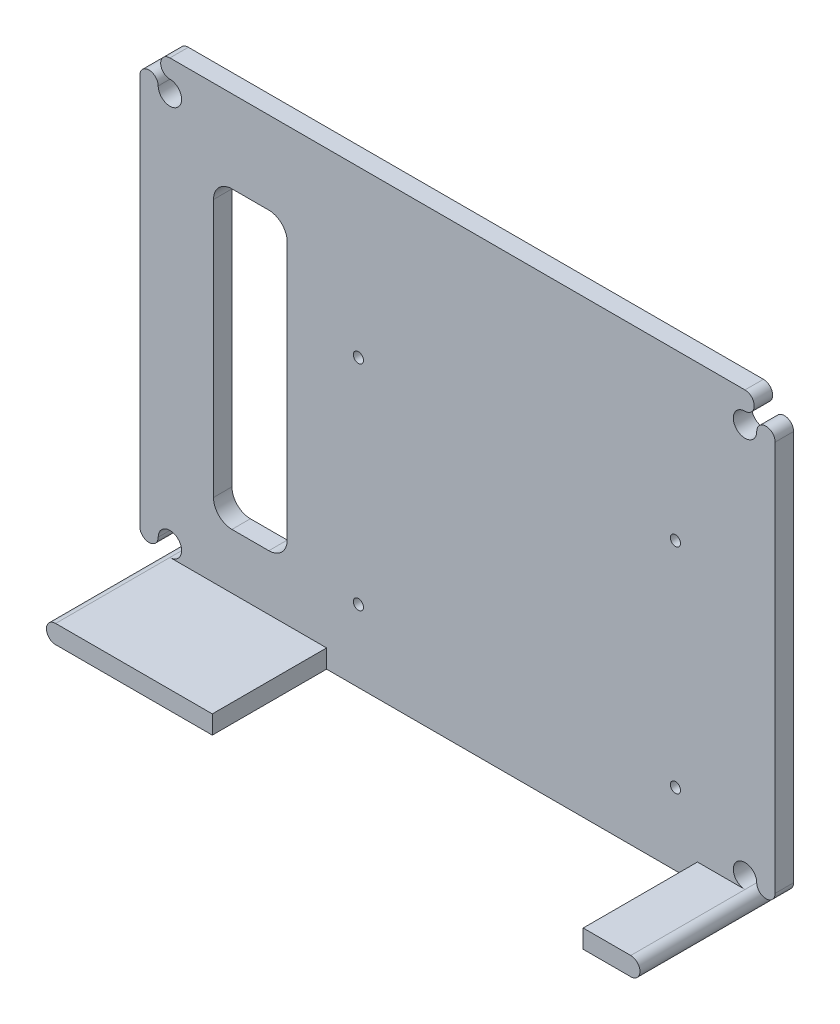
SolidWorks part; units mm, degrees
material "ABS"
ref_plane "Plano frontal" through (0, 0, 0) normal (0, 0, 1) x (1, 0, 0)
ref_plane "Plano superior" through (0, 0, 0) normal (0, 1, 0) x (1, 0, 0)
ref_plane "Plano direito" through (0, 0, 0) normal (1, 0, 0) x (0, 0, -1)
sketch "Esboço1" plane through (0, 0, 0) normal (0, 0, 1) x (1, 0, 0)
  line L6 (-78, -61.175) -> (78, -61.175)
  line L10 (-86.175, -53) -> (-86.175, 53)
  line L11 (-78, 61.175) -> (77.9912, 61.175)
  line L12 (86.175, -53) -> (86.175, 53)
  line L13 (-78, -53) -> (78, 53) construction
  line L14 (78, -53) -> (-78, 53) construction
  arc A0 (-81.175, 53) -> (-78, 56.175) centre (-78, 53) ccw
  arc A1 (-78, -56.175) -> (-81.175, -53) centre (-78, -53) ccw
  arc A2 (81.175, -53) -> (78, -56.175) centre (78, -53) ccw
  arc A3 (77.9966, 56.175) -> (81.175, 53) centre (78, 53) ccw
  arc A4 (81.175, 53) -> (86.175, 53) centre (83.675, 53) cw
  arc A5 (77.9966, 56.175) -> (77.9912, 61.175) centre (77.9939, 58.675) ccw
  arc A6 (86.175, -53) -> (81.175, -53) centre (83.675, -53) cw
  arc A7 (78, -56.175) -> (78, -61.175) centre (78, -58.675) cw
  arc A8 (-78, -56.175) -> (-78, -61.175) centre (-78, -58.675) ccw
  arc A9 (-81.175, -53) -> (-86.175, -53) centre (-83.675, -53) cw
  arc A10 (-86.175, 53) -> (-81.175, 53) centre (-83.675, 53) cw
  arc A11 (-78, 56.175) -> (-78, 61.175) centre (-78, 58.675) cw
  point P0 (0, 0)
  point P1 (0, 0)
  point P2 (0, 0)
  dimension "D3" = 3.175
  dimension "D4" = 106
  dimension "D5" = 5
  dimension "D6" = 5
  dimension "D7" = 5
  dimension "D1" = 2.5
  dimension "D2" = 156
  dimension "D8" = 5
  dimension "D9" = 5
  dimension "D10" = 5
  dimension "D11" = 5
  dimension "D12" = 5
  dimension "D13" = 8.0257
  dimension "D14" = 8.0257
  dimension "D15" = 8.03
extrude "Ressalto-extrusão1" add sketch "Esboço1" along normal blind 5
sketch "Esboço2" plane through (0, 0, 5) normal (0, 0, 1) x (1, 0, 0)
  line L0 (-78, -56.175) -> (-35.5, -56.175)
  line L3 (-35.5, -56.175) -> (-35.5, -60.2122)
  line L8 (78, -61.175) -> (65.0993, -61.175)
  line L9 (78, -56.175) -> (65.0993, -56.175)
  line L10 (65.0993, -56.175) -> (65.0993, -61.175)
  line L11 (-35.5, -60.2122) -> (-35.5, -61.175)
  line L12 (-78, -61.175) -> (78, -61.175) construction
  line L13 (-35.5, -61.175) -> (-78, -61.175)
  arc A0 (-78, -56.175) -> (-78, -61.175) centre (-78, -58.675) ccw
  arc A2 (78, -56.175) -> (78, -61.175) centre (78, -58.675) cw
  point P14 (-80.5, -58.675)
  dimension "D1" = 2.5
  dimension "D2" = 12.9007
  dimension "D3" = 45
extrude "Ressalto-extrusão2" add sketch "Esboço2" along normal blind 31
sketch "Esboço3" plane through (0, 0, 5) normal (0, 0, 1) x (1, 0, 0)
  line L0 (86.175, -53) -> (86.175, 53) construction
  line L1 (-35.5, -61.175) -> (65.0993, -61.175) construction
  circle A0 centre (59.1253, -41.6378) radius 1.38
  circle A1 centre (59.1253, 16.3622) radius 1.38
  circle A2 centre (-26.8747, -41.6378) radius 1.38
  circle A3 centre (-26.8747, 16.3622) radius 1.38
  dimension "D1" = 27.0497
  dimension "D2" = 19.5372
  dimension "D3" = 2.76
  dimension "D4" = 86
  dimension "D5" = 58
extrude "Corte-extrusão1" cut sketch "Esboço3" against normal blind 5
sketch "Esboço4" plane through (0, 0, 5) normal (0, 0, 1) x (1, 0, 0)
  line L0 (-78, -61.175) -> (-35.5, -61.175) construction
  line L1 (-61.175, 38.825) -> (-51.175, 38.825)
  line L2 (-66.175, 33.825) -> (-66.175, -36.175)
  line L3 (-61.175, -41.175) -> (-51.175, -41.175)
  line L4 (-46.175, 33.825) -> (-46.175, -36.175)
  line L5 (-86.175, 53) -> (-86.175, -53) construction
  arc A0 (-66.175, -36.175) -> (-61.175, -41.175) centre (-61.175, -36.175) ccw
  arc A1 (-51.175, -41.175) -> (-46.175, -36.175) centre (-51.175, -36.175) ccw
  arc A2 (-51.175, 38.825) -> (-46.175, 33.825) centre (-51.175, 33.825) cw
  arc A3 (-61.175, 38.825) -> (-66.175, 33.825) centre (-61.175, 33.825) ccw
  point P12 (-46.175, -41.175)
  point P15 (-46.175, 38.825)
  point P18 (-66.175, 38.825)
  dimension "D5" = 5
  dimension "D1" = 20
  dimension "D2" = 20
  dimension "D3" = 20
  dimension "D4" = 80
extrude "Corte-extrusão2" cut sketch "Esboço4" against normal up to surface (5 mm away) up to face at (60.5053, 16.3622, 0)
